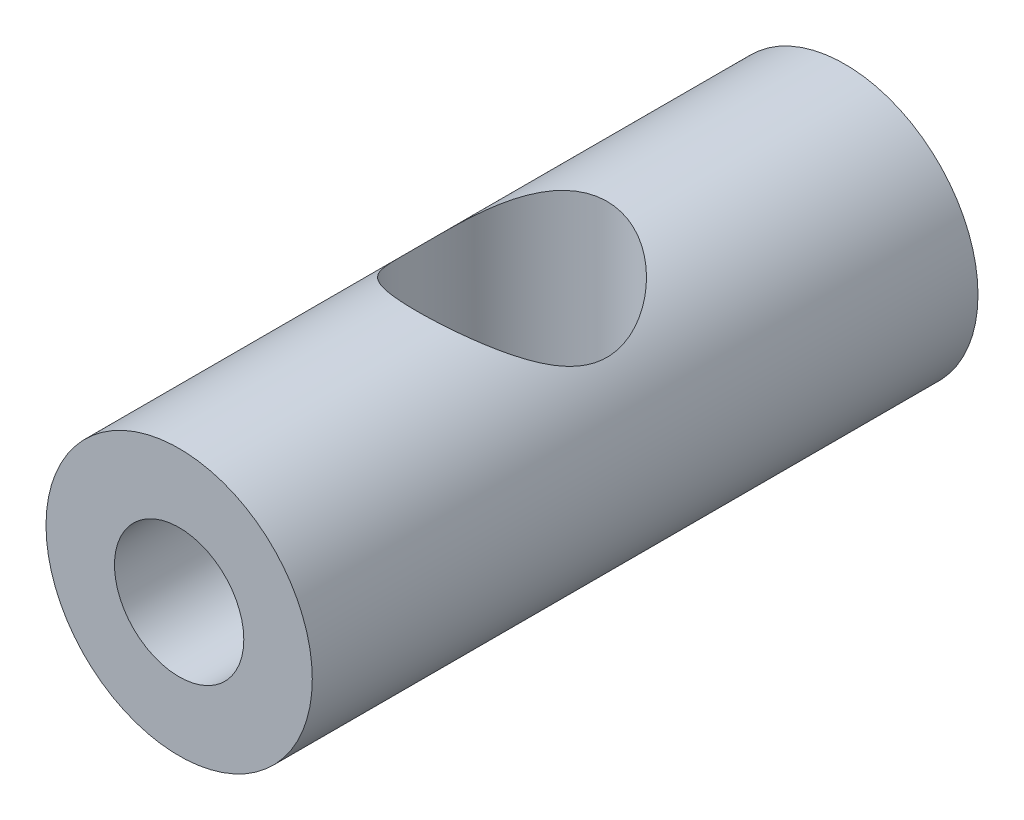
SolidWorks part; units mm, degrees
ref_plane "Plan de face" through (0, 0, 0) normal (0, 0, 1) x (1, 0, 0)
ref_plane "Plan de dessus" through (0, 0, 0) normal (0, 1, 0) x (1, 0, 0)
ref_plane "Plan de droite" through (0, 0, 0) normal (1, 0, 0) x (0, 0, -1)
sketch "Esquisse1" plane through (0, 0, 0) normal (0, 0, 1) x (1, 0, 0)
  circle A0 centre (0, 0) radius 7
  dimension "D1" = 14
extrude "Boss.-Extru.1" add sketch "Esquisse1" along normal mid plane 35
sketch "Esquisse2" plane through (0, 0, 0) normal (0, 1, 0) x (1, 0, 0)
  circle A0 centre (0, 0) radius 5
  dimension "D1" = 10
extrude "Enlèv. mat.-Extru.1" cut sketch "Esquisse2" against normal through all and the other way through all
hole_wizard "Trou taraudé M81" positions "Esquisse4" profile "Esquisse3" tap size "M8" standard "ISO"
sketch "Esquisse4" plane through (0, 0, 17.5) normal (0, 0, 1) x (1, 0, 0)
  point P0 (0, 0)
sketch "Esquisse3" plane through (0, 0, 17.5) normal (1, 0, 0) x (0, -1, 0)
  line L0 (0, 0) -> (0, 22.0429)
  line L1 (0, 22.0429) -> (3.4, 20)
  line L2 (3.4, 20) -> (3.4, 0)
  line L5 (3.4, 0) -> (0, 0)
  line L10 (0, 22.0429) -> (-3.4, 20) construction
  line L11 (0, -6.35) -> (0, 107.95) construction
  dimension "Diamètre du trou pour taraudage" = 6.8
  dimension "Profondeur du trou pour taraudage" = 20
  dimension "Angle de pointe" = 118
cosmetic thread "Filetage de perçage1" parameters "D1"=13.8339, "D2"=8
